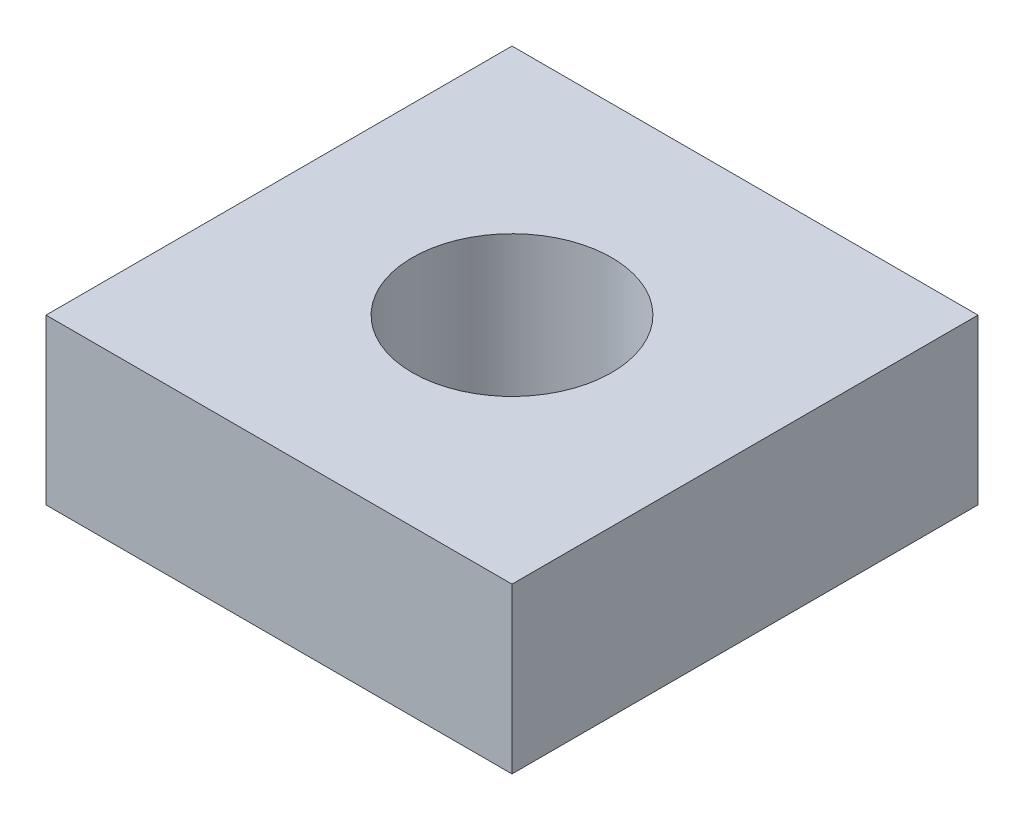
SolidWorks part; units mm, degrees
ref_plane "Front Plane" through (0, 0, 0) normal (0, 0, 1) x (1, 0, 0)
ref_plane "Top Plane" through (0, 0, 0) normal (0, 1, 0) x (1, 0, 0)
ref_plane "Right Plane" through (0, 0, 0) normal (1, 0, 0) x (0, 0, -1)
sketch "Sketch2" plane through (0, 0, 0) normal (0, 1, 0) x (1, 0, 0)
  line L0 (-9, 4.5) -> (0, 4.5) construction
  line L1 (0, 0) -> (-9, 0)
  line L2 (0, 0) -> (0, 9)
  line L3 (0, 9) -> (-9, 9)
  line L4 (-9, 0) -> (-9, 9)
  line L5 (-4.5, 0) -> (-4.5, 9) construction
  circle A1 centre (-4.5, 4.5) radius 1.925
  dimension "D1" = 3.85
  dimension "D2" = 9
extrude "Boss-Extrude1" add sketch "Sketch2" along normal blind 3.175
